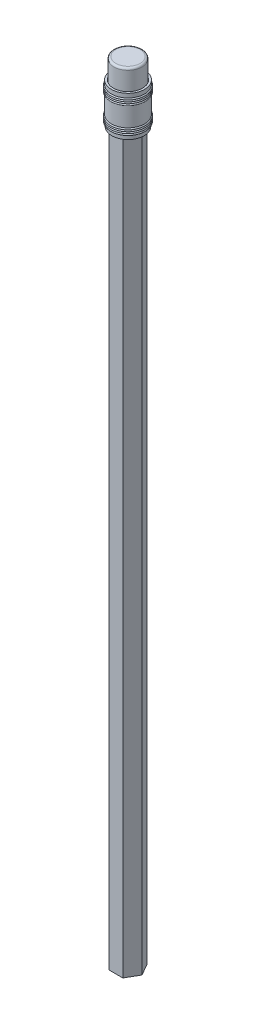
SolidWorks part; units mm, degrees
ref_plane "Front Plane" through (0, 0, 0) normal (0, 0, 1) x (1, 0, 0)
ref_plane "Top Plane" through (0, 0, 0) normal (0, 1, 0) x (1, 0, 0)
ref_plane "Right Plane" through (0, 0, 0) normal (1, 0, 0) x (0, 0, -1)
sketch "Sketch1" plane through (0, 0, 0) normal (0, 1, 0) x (1, 0, 0)
  circle A0 centre (0, 0) radius 1.25
  dimension "D1" = 2.5
extrude "Lead" add sketch "Sketch1" along normal blind 185
sketch "Sketch2" plane through (0, 0, 0) normal (0, -1, 0) x (1, 0, 0)
  line L1 (-3.4641, 0) -> (-1.7321, -3)
  line L2 (-1.7321, -3) -> (1.7321, -3)
  line L3 (1.7321, -3) -> (3.4641, 0)
  line L4 (3.4641, 0) -> (1.7321, 3)
  line L5 (1.7321, 3) -> (-1.7321, 3)
  line L6 (-1.7321, 3) -> (-3.4641, 0)
  circle A0 centre (0, 0) radius 3 construction
  circle A1 centre (0, 0) radius 1.25
  circle A3 centre (0, 0) radius 1.25 construction
  dimension "D1" = 6
extrude "Wooden Casing" add sketch "Sketch2" against normal up to surface (185 mm away) separate body up to face at (0, 185, 1.25)
sketch "Sketch3" plane through (0, 185, 0) normal (0, 1, 0) x (1, 0, 0)
  circle A0 centre (0, 0) radius 3.5
  dimension "D1" = 7
extrude "Eraser" add sketch "Sketch3" along normal blind 10 separate body
fillet "Fillet" radius 0.5 1 edges at (0, 195, 3.5)
sketch "Sketch4" plane through (0, 0, 0) normal (0, 0, 1) x (1, 0, 0)
  line L0 (0, 195) -> (0, 185) construction
  line L1 (3, 195) -> (-3, 195) construction
  line L2 (1.7321, 185) -> (-1.7321, 185) construction
  line L3 (-3.6, 181) -> (-3.6, 180.0006)
  line L4 (-4.1, 190) -> (-3.6, 190)
  line L5 (-4.1, 190) -> (-4.1, 188.9956) construction
  line L6 (-3.991, 180.0006) -> (-3.6, 180.0006)
  line L7 (-3.6, 190) -> (-3.6, 189)
  line L8 (-4.1, 190) -> (-4.1, 188.9956)
  line L10 (-4.1, 184.9956) -> (-4.1, 187.3956)
  line L13 (-4.1, 184.9956) -> (-4.1, 182.5956)
  line L14 (-3.991, 181.0279) -> (-3.991, 180.0006)
  line L15 (-3.6, 187.4) -> (-3.6, 182.6)
  line L19 (-3.6, 181) -> (-3.6, 180.0006) construction
  line L21 (-3.6, 187.4) -> (-3.6, 182.6) construction
  line L22 (-4.1, 187.3956) -> (-4.1, 182.5956) construction
  line L23 (-3.991, 181.0279) -> (-3.991, 180.0006) construction
  line L25 (-3.6, 190) -> (-3.6, 189) construction
  arc A0 (-4.1, 181.3956) -> (-3.991, 181.0279) centre (-4.1, 181.1956) ccw
  arc A1 (-4.1, 181.7956) -> (-4.1, 181.3956) centre (-4.1, 181.5956) ccw
  arc A2 (-4.1, 182.1956) -> (-4.1, 181.7956) centre (-4.1, 181.9956) ccw
  arc A3 (-4.1, 182.5956) -> (-4.1, 182.1956) centre (-4.1, 182.3956) ccw
  arc A4 (-4.1, 187.3956) -> (-4.1, 187.7956) centre (-4.1, 187.5956) cw
  arc A5 (-4.1, 187.7956) -> (-4.1, 188.1956) centre (-4.1, 187.9956) cw
  arc A6 (-4.1, 188.1956) -> (-4.1, 188.5956) centre (-4.1, 188.3956) cw
  arc A7 (-4.1, 188.5956) -> (-4.1, 188.9956) centre (-4.1, 188.7956) cw
  arc A8 (-3.6, 188.6) -> (-3.6, 189) centre (-3.6, 188.8) ccw
  arc A9 (-3.6, 188.2) -> (-3.6, 188.6) centre (-3.6, 188.4) ccw
  arc A10 (-3.6, 187.8) -> (-3.6, 188.2) centre (-3.6, 188) ccw
  arc A11 (-3.6, 187.4) -> (-3.6, 187.8) centre (-3.6, 187.6) ccw
  arc A12 (-3.6, 182.6) -> (-3.6, 182.2) centre (-3.6, 182.4) cw
  arc A13 (-3.6, 182.2) -> (-3.6, 181.8) centre (-3.6, 182) cw
  arc A14 (-3.6, 181.8) -> (-3.6, 181.4) centre (-3.6, 181.6) cw
  arc A15 (-3.6, 181.4) -> (-3.6, 181) centre (-3.6, 181.2) cw
  point P30 (0, 0)
  point P32 (0, 0)
  point P33 (0, 0)
  point P36 (-3.5948, 188.4008)
  point P54 (0, 0)
  point P55 (-4.0988, 188.4051)
  point P56 (0, 0)
  point P57 (-3.5991, 188.4051)
  point P58 (-3.5999, 188.4009)
  dimension "D5" = 1
  dimension "D6" = 0.2
  dimension "D1" = 10
  dimension "D2" = 5
  dimension "D3" = 0.5
  dimension "D4" = 4.1
  dimension "D8" = 0.4
revolve "Revolve6" add sketch "Sketch4" angle 360 about L0
